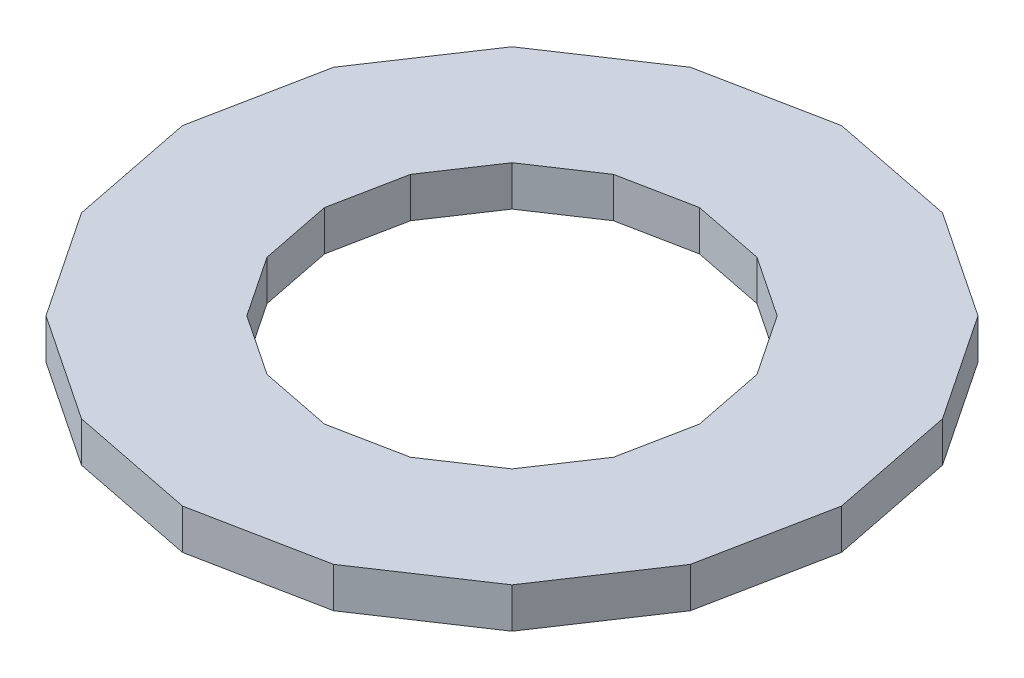
SolidWorks part; units mm, degrees
ref_plane "Front Plane" through (0, 0, 0) normal (0, 0, 1) x (1, 0, 0)
ref_plane "Top Plane" through (0, 0, 0) normal (0, 1, 0) x (1, 0, 0)
ref_plane "Right Plane" through (0, 0, 0) normal (1, 0, 0) x (0, 0, -1)
sketch "Sketch1" plane through (0, 0, 0) normal (0, 1, 0) x (1, 0, 0)
  line L1 (88.9015, 0) -> (82.1343, 34.0211)
  line L2 (82.1343, 34.0211) -> (62.8629, 62.8629)
  line L3 (62.8629, 62.8629) -> (34.0211, 82.1343)
  line L4 (34.0211, 82.1343) -> (0, 88.9015)
  line L5 (0, 88.9015) -> (-34.0211, 82.1343)
  line L6 (-34.0211, 82.1343) -> (-62.8629, 62.8629)
  line L7 (-62.8629, 62.8629) -> (-82.1343, 34.0211)
  line L8 (-82.1343, 34.0211) -> (-88.9015, 0)
  line L9 (-88.9015, 0) -> (-82.1343, -34.0211)
  line L10 (-82.1343, -34.0211) -> (-62.8629, -62.8629)
  line L11 (-62.8629, -62.8629) -> (-34.0211, -82.1343)
  line L12 (-34.0211, -82.1343) -> (0, -88.9015)
  line L13 (0, -88.9015) -> (34.0211, -82.1343)
  line L14 (34.0211, -82.1343) -> (62.8629, -62.8629)
  line L15 (62.8629, -62.8629) -> (82.1343, -34.0211)
  line L16 (82.1343, -34.0211) -> (88.9015, 0)
  line L17 (156.2353, 0) -> (144.3426, 59.7887)
  line L18 (144.3426, 59.7887) -> (110.4751, 110.4751)
  line L19 (110.4751, 110.4751) -> (59.7887, 144.3426)
  line L20 (59.7887, 144.3426) -> (0, 156.2353)
  line L21 (0, 156.2353) -> (-59.7887, 144.3426)
  line L22 (-59.7887, 144.3426) -> (-110.4751, 110.4751)
  line L23 (-110.4751, 110.4751) -> (-144.3426, 59.7887)
  line L24 (-144.3426, 59.7887) -> (-156.2353, 0)
  line L25 (-156.2353, 0) -> (-144.3426, -59.7887)
  line L26 (-144.3426, -59.7887) -> (-110.4751, -110.4751)
  line L27 (-110.4751, -110.4751) -> (-59.7887, -144.3426)
  line L28 (-59.7887, -144.3426) -> (0, -156.2353)
  line L29 (0, -156.2353) -> (59.7887, -144.3426)
  line L30 (59.7887, -144.3426) -> (110.4751, -110.4751)
  line L31 (110.4751, -110.4751) -> (144.3426, -59.7887)
  line L32 (144.3426, -59.7887) -> (156.2353, 0)
  circle A1 centre (0, 0) radius 87.1933 construction
  circle A2 centre (0, 0) radius 153.2333 construction
  dimension "D1" = 66.04
  dimension "D2" = 60.96
extrude "Boss-Extrude1" add sketch "Sketch1" along normal blind 19.05
